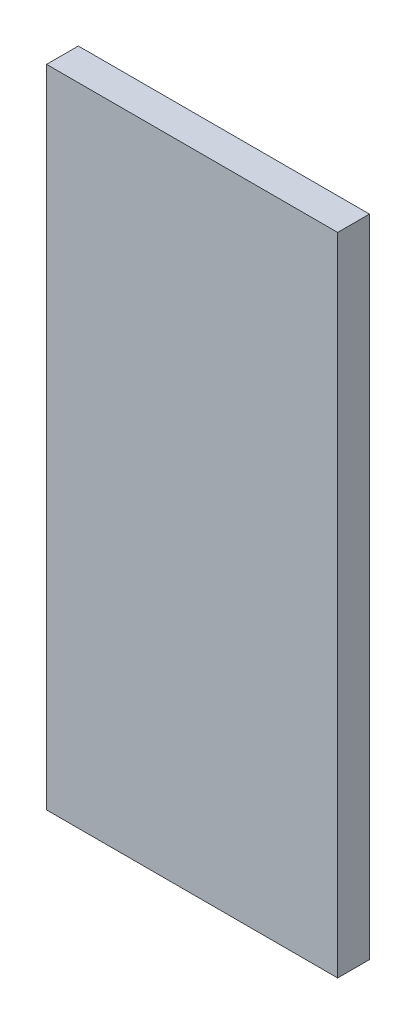
SolidWorks part; units mm, degrees
material "Beech"
ref_plane "Front Plane" through (0, 0, 0) normal (0, 0, 1) x (1, 0, 0)
ref_plane "Top Plane" through (0, 0, 0) normal (0, 1, 0) x (1, 0, 0)
ref_plane "Right Plane" through (0, 0, 0) normal (1, 0, 0) x (0, 0, -1)
sketch "Sketch1" plane through (0, 0, 0) normal (0, 0, 1) x (1, 0, 0)
  line L1 (-13.75, 30.5) -> (13.75, 30.5)
  line L2 (-13.75, 30.5) -> (-13.75, -30.5)
  line L3 (-13.75, -30.5) -> (13.75, -30.5)
  line L4 (13.75, 30.5) -> (13.75, -30.5)
  line L5 (-13.75, 30.5) -> (13.75, -30.5) construction
  line L6 (-13.75, -30.5) -> (13.75, 30.5) construction
  point P0 (0, 0)
  dimension "D1" = 27.5
  dimension "D2" = 61
extrude "Boss-Extrude1" add sketch "Sketch1" along normal blind 3
